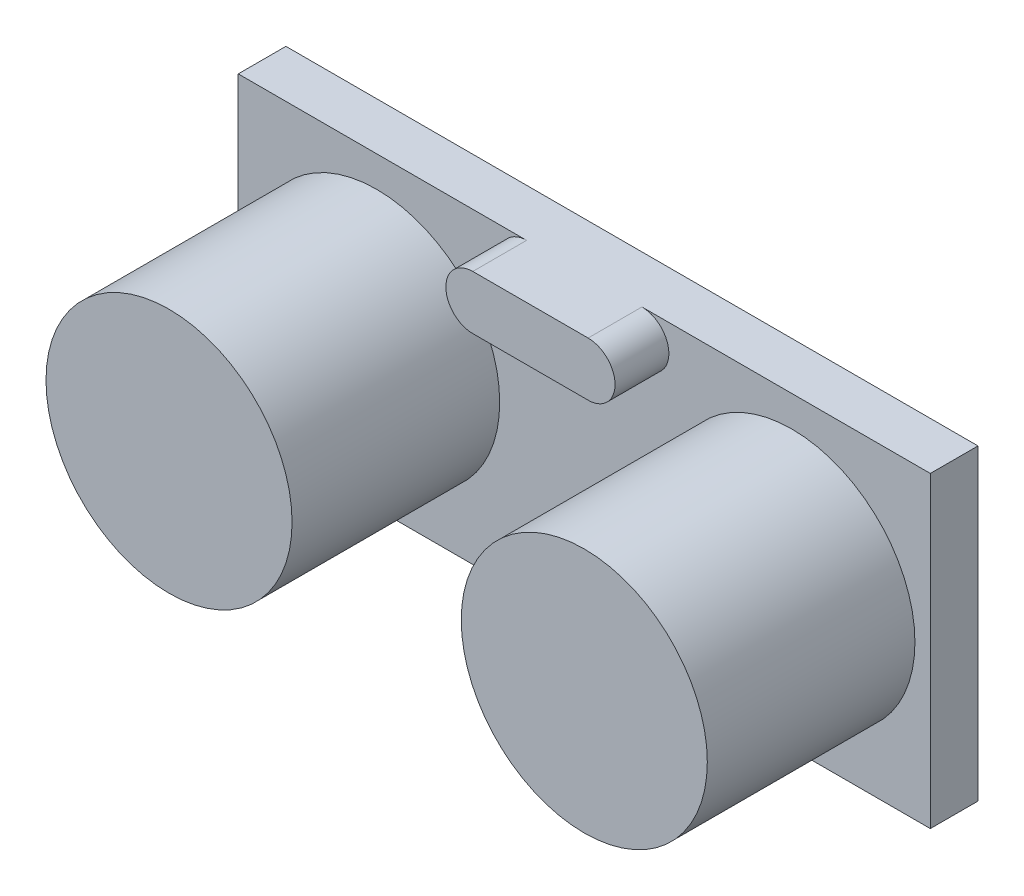
SolidWorks part; units mm, degrees
ref_plane "Piano frontale" through (0, 0, 0) normal (0, 0, 1) x (1, 0, 0)
ref_plane "Piano superiore" through (0, 0, 0) normal (0, 1, 0) x (1, 0, 0)
ref_plane "Piano destro" through (0, 0, 0) normal (1, 0, 0) x (0, 0, -1)
sketch "Schizzo1" plane through (0, 0, 0) normal (0, 0, 1) x (1, 0, 0)
  line L1 (0, 0) -> (45, 0)
  line L2 (0, 0) -> (0, 20)
  line L3 (0, 20) -> (45, 20)
  line L4 (45, 0) -> (45, 20)
  dimension "D1" = 45
  dimension "D2" = 20
extrude "Estrusione-Estrusione1" add sketch "Schizzo1" along normal blind 3.1
sketch "Schizzo2" plane through (0, 0, 3.1) normal (0, 0, 1) x (1, 0, 0)
  line L0 (0, 20) -> (0, 0) construction
  line L1 (45, 20) -> (0, 20) construction
  circle A0 centre (9, 10) radius 8
  circle A1 centre (36, 10) radius 8
  dimension "D1" = 16
  dimension "D2" = 16
  dimension "D3" = 27
  dimension "D4" = 10
  dimension "D5" = 9
extrude "Estrusione-Estrusione2" add sketch "Schizzo2" along normal blind 13.5
sketch "Schizzo3" plane through (0, 0, 0) normal (0, 0, -1) x (-1, 0, 0)
  line L0 (-45, 0) -> (-45, 20) construction
  line L1 (0, 0) -> (-45, 0) construction
  line L3 (-26.25, 0) -> (-18.75, 0)
  line L4 (-26.25, 0) -> (-26.25, 3)
  line L5 (-26.25, 3) -> (-18.75, 3)
  line L6 (-18.75, 0) -> (-18.75, 3)
  point P5 (-21.9614, 0)
  dimension "D1" = 7.5
  dimension "D2" = 18.75
  dimension "D3" = 3
extrude "Estrusione-Estrusione3" add sketch "Schizzo3" along normal blind 4
sketch "Schizzo4" plane through (0, 0, 3.1) normal (0, 0, 1) x (1, 0, 0)
  line L5 (18.75, 18.25) -> (26.25, 18.25) construction
  line L10 (18.75, 20) -> (26.25, 20)
  line L11 (18.75, 16.5) -> (26.25, 16.5)
  line L12 (45, 20) -> (0, 20) construction
  arc A0 (18.75, 20) -> (18.75, 16.5) centre (18.75, 18.25) ccw
  arc A1 (26.25, 16.5) -> (26.25, 20) centre (26.25, 18.25) ccw
  point P3 (22.5, 20)
  point P4 (22.5, 20)
  point P10 (22.5, 18.25)
  dimension "D1" = 3.5
  dimension "D2" = 7.5
extrude "Estrusione-Estrusione4" add sketch "Schizzo4" along normal blind 3.5
sketch "Schizzo5" plane through (0, 0, 0) normal (0, -1, 0) x (1, 0, 0)
  line L0 (26.25, -4) -> (26.25, 0) construction
  line L1 (18.75, -4) -> (26.25, -4)
  line L2 (18.75, -4) -> (18.75, -1.5)
  line L3 (18.75, -1.5) -> (26.25, -1.5)
  line L4 (26.25, -4) -> (26.25, -1.5)
  dimension "D1" = 2.5
extrude "Estrusione-Estrusione5" add sketch "Schizzo5" along normal blind 7
